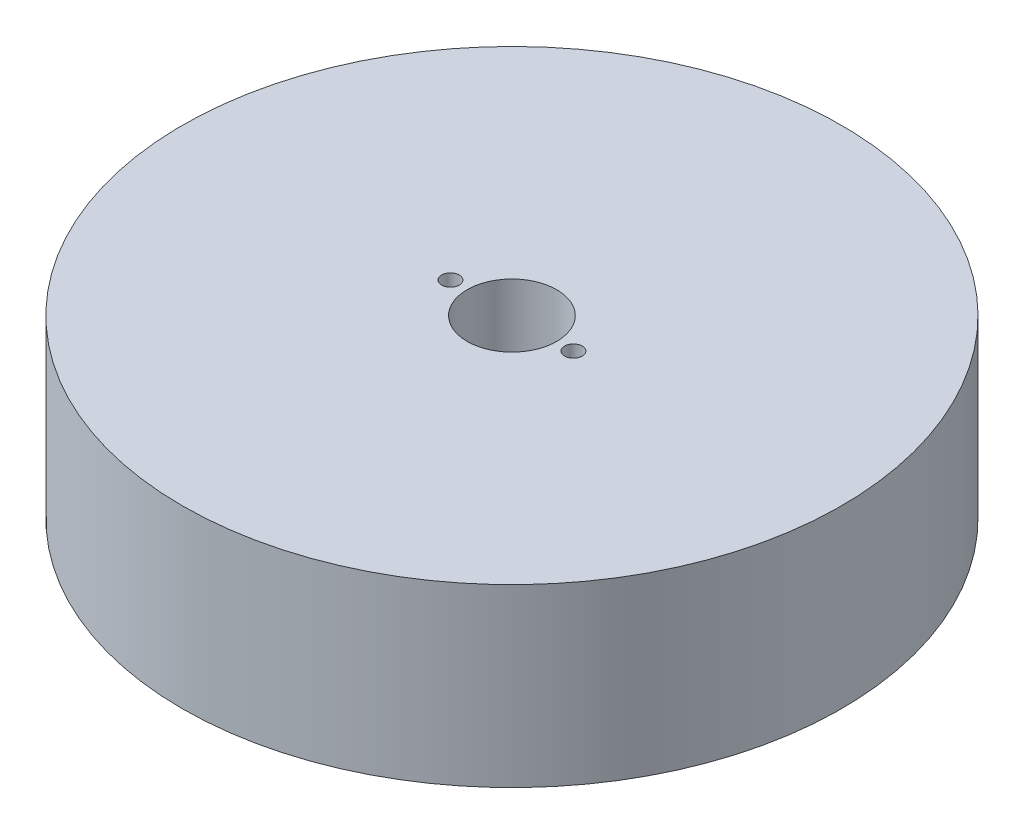
SolidWorks part; units mm, degrees
ref_plane "Front Plane" through (0, 0, 0) normal (0, 0, 1) x (1, 0, 0)
ref_plane "Top Plane" through (0, 0, 0) normal (0, 1, 0) x (1, 0, 0)
ref_plane "Right Plane" through (0, 0, 0) normal (1, 0, 0) x (0, 0, -1)
sketch "Sketch1" plane through (0, 0, 0) normal (0, 1, 0) x (1, 0, 0)
  circle A0 centre (0, 0) radius 5.1
  circle A1 centre (0, 0) radius 37.5
  circle A2 centre (-7, 0) radius 1
  circle A3 centre (7, 0) radius 1
  circle A4 centre (0, 0) radius 7 construction
  dimension "D1" = 10.2
  dimension "D2" = 75
  dimension "D3" = 14
  dimension "D4" = 2
extrude "Boss-Extrude1" add sketch "Sketch1" along normal blind 20
equation "\"Height\"= 20"
equation "\"Alignment Pin Diameter\"= 2"
equation "\"Shaft OD\"= 10.2"
equation "\"Alignment Pin Circle Diameter\"= 14"
equation "\"D1@Sketch1\"=\"Shaft OD\""
equation "\"D3@Sketch1\"= \"Alignment Pin Circle Diameter\""
equation "\"D4@Sketch1\"=\"Alignment Pin Diameter\""
equation "\"D1@Boss-Extrude1\"=\"Height\""
equation "\"Diameter\"= 75"
equation "\"D2@Sketch1\"= \"Diameter\""
